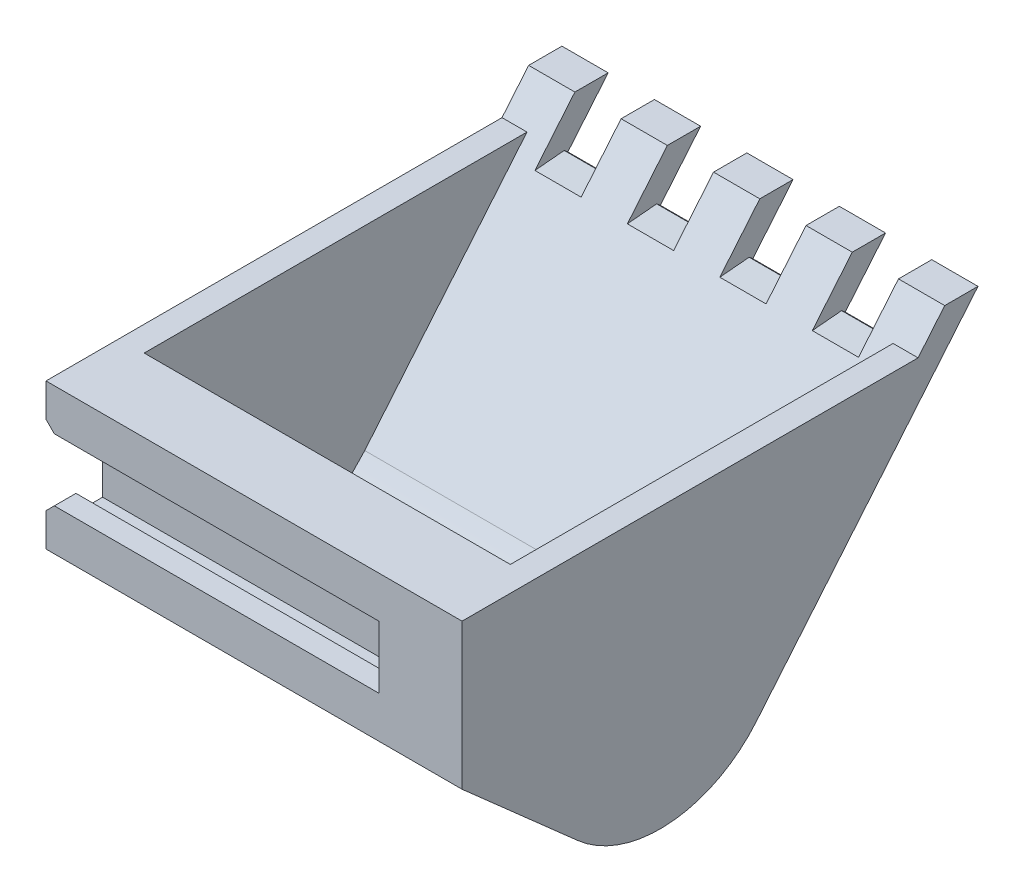
SolidWorks part; units mm, degrees
material "CA"
ref_plane "Front Plane" through (0, 0, 0) normal (0, 0, 1) x (1, 0, 0)
ref_plane "Top Plane" through (0, 0, 0) normal (0, 1, 0) x (1, 0, 0)
ref_plane "Right Plane" through (0, 0, 0) normal (1, 0, 0) x (0, 0, -1)
sketch "Sketch1" plane through (0, 0, 0) normal (1, 0, 0) x (0, 0, -1)
  line L0 (0, 0) -> (50, 0)
  line L7 (16.6667, -40) -> (50, 0)
  line L8 (-8.8, -5) -> (-6.2, -5)
  line L10 (-8.8, -12.5) -> (-6.2, -12.5)
  line L12 (-6.2, -3) -> (-3, -3)
  line L13 (-6.2, -3) -> (-6.2, -5)
  line L14 (-6.2, -14.5) -> (-3, -14.5)
  line L15 (-3, -3) -> (-3, -14.5)
  line L16 (-6.2, -12.5) -> (-6.2, -14.5)
  line L17 (0, 0) -> (-8.8, 0)
  line L18 (-8.8, 0) -> (-8.8, -5)
  line L19 (-8.8, -12.5) -> (-8.8, -17.5)
  line L20 (-8.8, -17.5) -> (16.6667, -40)
  point P6 (16.6667, -40)
  dimension "D1" = 50
  dimension "D2" = 16.6667
  dimension "D3" = 40
  dimension "D5" = 3.2
  dimension "D6" = 11.5
  dimension "D7" = 7.5
  dimension "D8" = 2.6
  dimension "D4" = 3
  dimension "D9" = 3
  dimension "D10" = 3
extrude "Boss-Extrude1" add sketch "Sketch1" along normal blind 50
sketch "Sketch2" plane through (50, 0, 0) normal (1, 0, 0) x (0, 0, -1)
  line L1 (-8.8, 0) -> (-0.8, 0)
  line L2 (-8.8, 0) -> (-8.8, -17.5)
  line L3 (-8.8, -17.5) -> (-0.8, -17.5)
  line L4 (-0.8, 0) -> (-0.8, -17.5)
  dimension "D1" = 8
extrude "Boss-Extrude2" add sketch "Sketch2" against normal blind 10
fillet "Fillet1" radius 15 1 edges at (25, -40, -16.6667)
sketch "Sketch3" plane through (50, 0, 0) normal (1, 0, 0) x (0, 0, -1)
  line L0 (50, 0) -> (46, 0) construction
  line L1 (50, 0) -> (-8.8, 0) construction
  line L2 (46, 0) -> (26.5016, -23.398)
  line L4 (0, -15) -> (0, 0)
  line L5 (26.5509, -28.1389) -> (50, 0) construction
  line L6 (0, 0) -> (46, 0)
  spline S0 degree 2 poles (0, -15) (11.3331, -40.237) (26.5016, -23.398) knots 0 0 0 1 1 1
  dimension "D4" = 15
  dimension "D1" = 4
  dimension "D2" = 3.0729
  dimension "D3" = 3.0729
extrude "Cut-Extrude1" cut sketch "Sketch3" against normal offset from surface (44 mm away) 3 from offset 3 up to face at (0, -11.5347, -1.2302) offset against normal yes
fillet "Fillet2" radius 15 1 edges at (25, -15, 0)
sketch "Sketch4" plane through (50, 0, 0) normal (1, 0, 0) x (0, 0, -1)
  line L0 (50, 0) -> (46, 0)
  line L1 (50, 0) -> (-8.8, 0) construction
  line L2 (50, 0) -> (53.2009, 3.8411)
  line L3 (53.2009, 3.8411) -> (49.2009, 3.8411)
  line L4 (49.2009, 3.8411) -> (46, 0)
  line L5 (26.5509, -28.1389) -> (50, 0) construction
  dimension "D1" = 4
  dimension "D2" = 4
  dimension "D3" = 180
  dimension "D4" = 5
extrude "Boss-Extrude3" add sketch "Sketch4" against normal through all
sketch "Sketch5" plane through (0, -22.623, -27.1475) normal (0, 0.6402, 0.7682) x (1, 0, 0)
  line L0 (11.1111, 37.0092) -> (11.1111, 29.4485)
  line L1 (0, 37.0092) -> (50, 37.0092) construction
  line L2 (0, 37.0092) -> (0, 29.4485) construction
  line L3 (0, 29.4485) -> (50, 29.4485) construction
  line L4 (50, 37.0092) -> (50, 29.4485) construction
  line L5 (0, 37.0092) -> (5.5556, 37.0092)
  line L6 (0, 37.0092) -> (0, 29.4485)
  line L7 (0, 29.4485) -> (5.5556, 29.4485)
  line L8 (5.5556, 37.0092) -> (5.5556, 29.4485)
  line L9 (11.1111, 37.0092) -> (16.6667, 37.0092)
  line L10 (16.6667, 37.0092) -> (16.6667, 29.4485)
  line L11 (11.1111, 29.4485) -> (16.6667, 29.4485)
  line L12 (22.2222, 37.0092) -> (22.2222, 29.4485)
  line L13 (22.2222, 37.0092) -> (27.7778, 37.0092)
  line L14 (27.7778, 37.0092) -> (27.7778, 29.4485)
  line L15 (22.2222, 29.4485) -> (27.7778, 29.4485)
  line L16 (33.3333, 37.0092) -> (33.3333, 29.4485)
  line L17 (33.3333, 37.0092) -> (38.8889, 37.0092)
  line L18 (38.8889, 37.0092) -> (38.8889, 29.4485)
  line L19 (33.3333, 29.4485) -> (38.8889, 29.4485)
  line L20 (44.4444, 37.0092) -> (44.4444, 29.4485)
  line L21 (44.4444, 37.0092) -> (50, 37.0092)
  line L22 (50, 37.0092) -> (50, 29.4485)
  line L23 (44.4444, 29.4485) -> (50, 29.4485)
  line L25 (5.5556, 37.0092) -> (11.1111, 37.0092)
  line L26 (5.5556, 37.0092) -> (5.5556, 29.4485)
  line L27 (5.5556, 29.4485) -> (11.1111, 29.4485)
  line L28 (11.1111, 37.0092) -> (11.1111, 29.4485)
  line L29 (16.6667, 37.0092) -> (22.2222, 37.0092)
  line L30 (16.6667, 37.0092) -> (16.6667, 29.4485)
  line L31 (16.6667, 29.4485) -> (22.2222, 29.4485)
  line L32 (22.2222, 37.0092) -> (22.2222, 29.4485)
  line L33 (27.7778, 37.0092) -> (33.3333, 37.0092)
  line L34 (27.7778, 37.0092) -> (27.7778, 29.4485)
  line L35 (27.7778, 29.4485) -> (33.3333, 29.4485)
  line L36 (33.3333, 37.0092) -> (33.3333, 29.4485)
  line L37 (38.8889, 37.0092) -> (44.4444, 37.0092)
  line L38 (38.8889, 37.0092) -> (38.8889, 29.4485)
  line L39 (38.8889, 29.4485) -> (44.4444, 29.4485)
  line L40 (44.4444, 37.0092) -> (44.4444, 29.4485)
  dimension "D1" = 5.5556
  dimension "D2" = 5
extrude "Cut-Extrude2" cut sketch "Sketch5" against normal through all contours L25 L8 L15 L0 | L8 L27 L0 L15 | L29 L10 L15 L12 | L10 L31 L12 L15 | L33 L14 L15 L16 | L14 L35 L16 L15 | L37 L18 L15 L20 | L18 L39 L20 L15
chamfer "Chamfer1" distance 2.5 angle 45 4 edges at (41.6667, 0, -46) (30.5556, 0, -46) (19.4444, 0, -46) (8.3333, 0, -46)
chamfer "Chamfer2" distance 1 angle 45 7 edges at (0, -12.5, 7.5) (0, -13.5, 6.2) (0, -14.5, 4.6) (0, -8.75, 3) (0, -3, 4.6) (0, -4, 6.2) (0, -5, 7.5)
equation "\"D2@Sketch1\"=\"D1@Sketch1\"/3"
